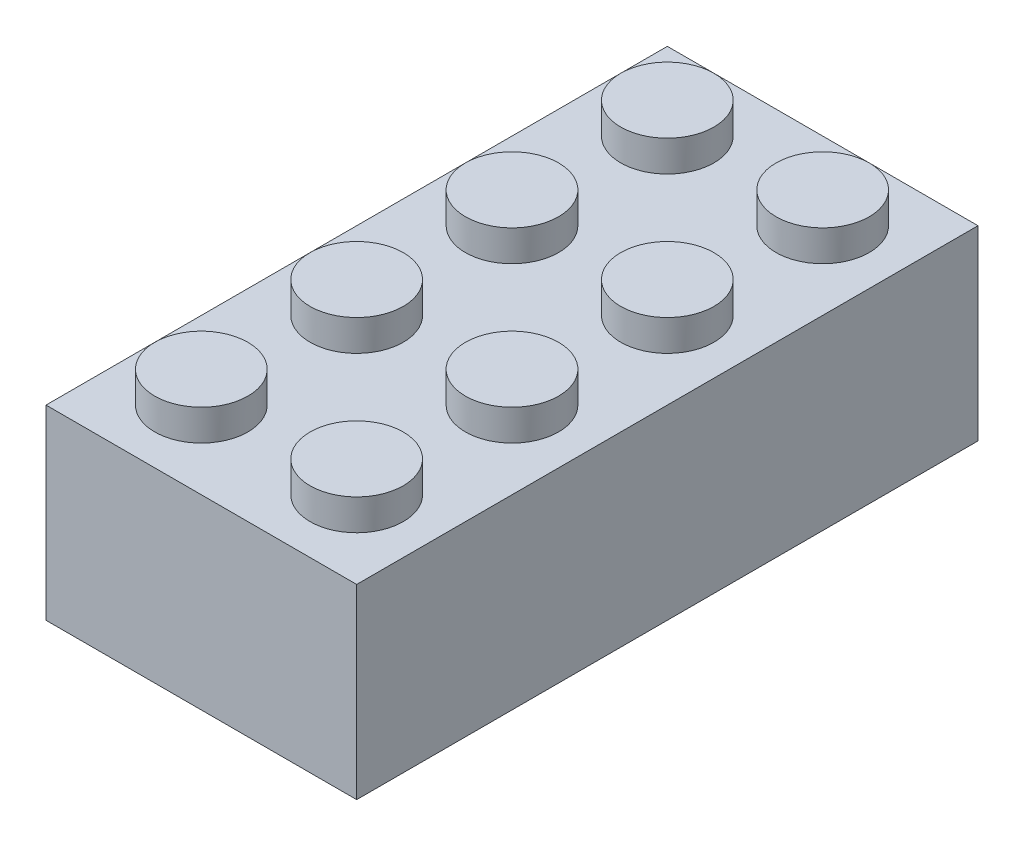
SolidWorks part; units mm, degrees
ref_plane "Front Plane" through (0, 0, 0) normal (0, 0, 1) x (1, 0, 0)
ref_plane "Top Plane" through (0, 0, 0) normal (0, 1, 0) x (1, 0, 0)
ref_plane "Right Plane" through (0, 0, 0) normal (1, 0, 0) x (0, 0, -1)
sketch "Sketch1" plane through (0, 0, 0) normal (0, 1, 0) x (1, 0, 0)
  line L1 (0, 0) -> (16, 0)
  line L2 (0, 0) -> (0, 32)
  line L3 (0, 32) -> (16, 32)
  line L4 (16, 0) -> (16, 32)
  dimension "D1" = 16
  dimension "D2" = 32
extrude "Boss-Extrude1" add sketch "Sketch1" along normal blind 9.6
sketch "Sketch2" plane through (0, 9.6, 0) normal (0, 1, 0) x (1, 0, 0)
  line L0 (8, 0) -> (8, 32) construction
  line L1 (0, 0) -> (16, 0) construction
  line L2 (16, 32) -> (0, 32) construction
  line L3 (16, 0) -> (16, 4) construction
  line L4 (16, 0) -> (16, 32) construction
  line L5 (16, 4) -> (12, 4) construction
  circle A0 centre (12, 4) radius 2.4
  dimension "D3" = 4.8
  dimension "D1" = 4
  dimension "D2" = 4
extrude "Boss-Extrude2" add sketch "Sketch2" along normal blind 1.6
pattern_linear "LPattern1" count 2 spacing 8 along (-1, 0, 0) count 4 spacing 8 along (0, 0, -1) of "Boss-Extrude2"
shell "Shell1" thickness 1.6
